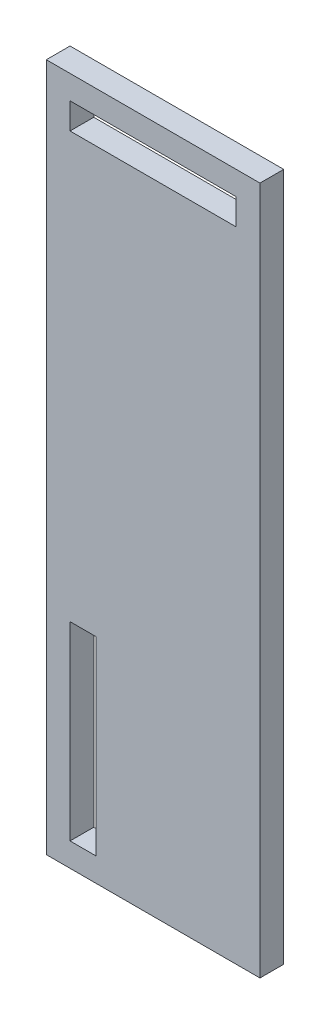
SolidWorks part; units mm, degrees
ref_plane "Front Plane" through (0, 0, 0) normal (0, 0, 1) x (1, 0, 0)
ref_plane "Top Plane" through (0, 0, 0) normal (0, 1, 0) x (1, 0, 0)
ref_plane "Right Plane" through (0, 0, 0) normal (1, 0, 0) x (0, 0, -1)
sketch "Sketch2" plane through (0, 0, 0) normal (0, 0, 1) x (1, 0, 0)
  line L1 (28.575, 92.075) -> (-28.575, 92.075)
  line L2 (28.575, 92.075) -> (28.575, -92.075)
  line L3 (28.575, -92.075) -> (-28.575, -92.075)
  line L4 (-28.575, 92.075) -> (-28.575, -92.075)
  point P4 (0, 92.075)
  point P6 (-28.575, 0)
  dimension "D2" = 57.15
  dimension "D3" = 184.15
extrude "Boss-Extrude1" add sketch "Sketch2" along normal blind 6.35
sketch "Sketch3" plane through (0, 0, 6.35) normal (0, 0, 1) x (1, 0, 0)
  line L0 (28.575, 92.075) -> (-28.575, 92.075) construction
  line L1 (-22.225, 78.74) -> (22.225, 78.74)
  line L2 (-22.225, 78.74) -> (-22.225, 85.725)
  line L4 (-22.225, 85.725) -> (22.225, 85.725)
  line L5 (22.225, 78.74) -> (22.225, 85.725)
  line L6 (-22.225, 78.74) -> (22.225, 85.725) construction
  line L7 (-22.225, 85.725) -> (22.225, 78.74) construction
  line L8 (28.575, -92.075) -> (28.575, 92.075) construction
  point P0 (0, 82.2325)
  dimension "D3" = 6.35
  dimension "D1" = 6.985
  dimension "D2" = 6.35
extrude "Cut-Extrude1" cut sketch "Sketch3" against normal through all
sketch "Sketch4" plane through (0, 0, 6.35) normal (0, 0, 1) x (1, 0, 0)
  line L0 (-28.575, -92.075) -> (28.575, -92.075) construction
  line L1 (-22.225, -34.925) -> (-15.24, -34.925)
  line L2 (-22.225, -34.925) -> (-22.225, -85.725)
  line L3 (-22.225, -85.725) -> (-15.24, -85.725)
  line L4 (-15.24, -34.925) -> (-15.24, -85.725)
  line L5 (-22.225, -34.925) -> (-15.24, -85.725) construction
  line L6 (-22.225, -85.725) -> (-15.24, -34.925) construction
  line L7 (-28.575, 92.075) -> (-28.575, -92.075) construction
  point P0 (-18.7325, -60.325)
  dimension "D1" = 6.35
  dimension "D2" = 6.985
  dimension "D3" = 50.8
  dimension "D4" = 6.35
extrude "Cut-Extrude2" cut sketch "Sketch4" against normal through all
